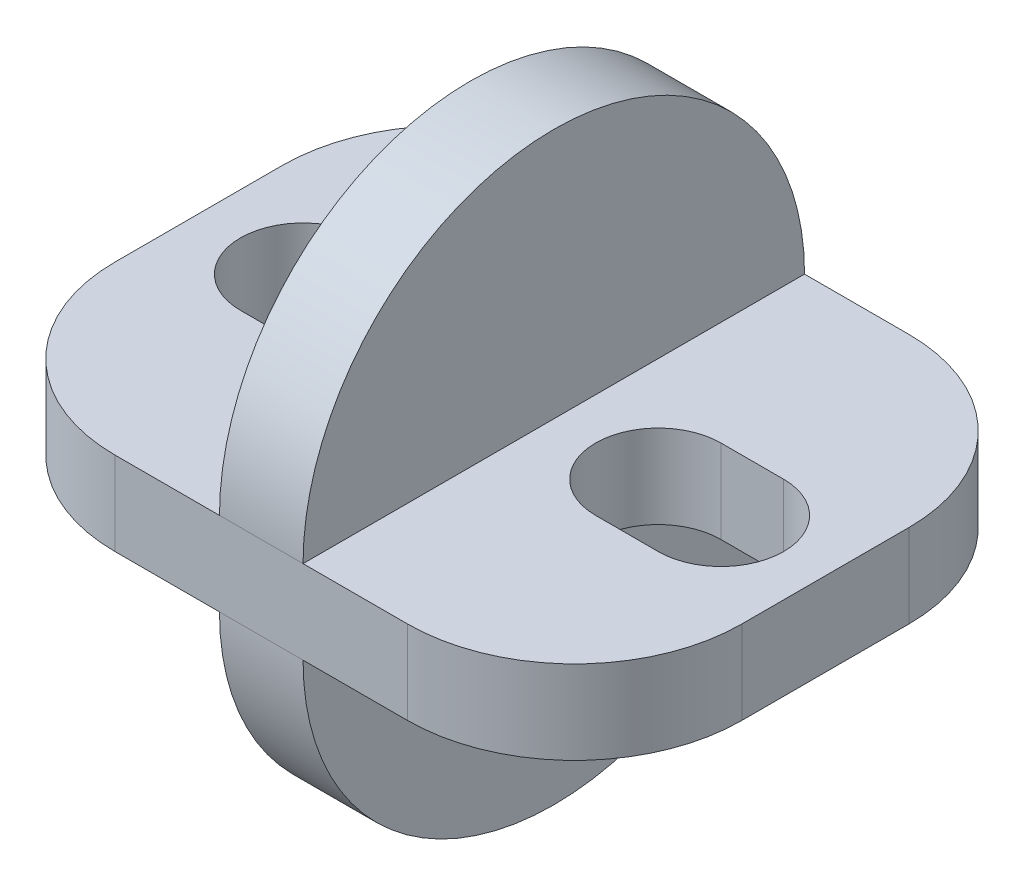
SolidWorks part; units mm, degrees
ref_plane "Alzado" through (0, 0, 0) normal (0, 0, 1) x (1, 0, 0)
ref_plane "Planta" through (0, 0, 0) normal (0, 1, 0) x (1, 0, 0)
ref_plane "Vista lateral" through (0, 0, 0) normal (1, 0, 0) x (0, 0, -1)
sketch "Croquis1" plane through (0, 0, 0) normal (0, 1, 0) x (1, 0, 0)
  line L1 (75, -60) -> (-75, -60)
  line L2 (75, -60) -> (75, 60)
  line L3 (75, 60) -> (-75, 60)
  line L4 (-75, -60) -> (-75, 60)
  line L5 (75, -60) -> (-75, 60) construction
  line L6 (75, 60) -> (-75, -60) construction
  point P0 (0, 0)
  dimension "D1" = 150
  dimension "D2" = 120
extrude "Saliente-Extruir1" add sketch "Croquis1" along normal blind 20
fillet "Redondeo1" radius 40 4 edges at (75, 10, 60) (75, 10, -60) (-75, 10, -60) (-75, 10, 60)
sketch "Croquis3" plane through (0, 0, 0) normal (1, 0, 0) x (0, 0, -1)
  line L0 (-60, 20) -> (60, 20)
  line L1 (60, 0) -> (-60, 0)
  arc A0 (-60, 20) -> (60, 20) centre (0, 20) cw
  arc A2 (-60, 0) -> (60, 0) centre (0, 0) ccw
  dimension "D1" = 60
  dimension "D2" = 60
extrude "Saliente-Extruir3" add sketch "Croquis3" along normal mid plane 20
sketch "Croquis4" plane through (0, 20, 0) normal (0, 1, 0) x (1, 0, 0)
  line L0 (-50, 0) -> (-35, 0) construction
  line L1 (-50, 15) -> (-35, 15)
  line L2 (-50, -15) -> (-35, -15)
  line L3 (50, 0) -> (35, 0) construction
  line L4 (50, -15) -> (35, -15)
  line L5 (50, 15) -> (35, 15)
  line L6 (-10, -60) -> (-10, 60) construction
  line L7 (10, -60) -> (10, 60) construction
  arc A0 (-50, 15) -> (-50, -15) centre (-50, 0) ccw
  arc A1 (-35, -15) -> (-35, 15) centre (-35, 0) ccw
  arc A2 (50, -15) -> (50, 15) centre (50, 0) ccw
  arc A3 (35, 15) -> (35, -15) centre (35, 0) ccw
  point P3 (-42.5, 0)
  point P8 (42.5, 0)
  dimension "D4" = 15
  dimension "D6" = 15
  dimension "D1" = 25
  dimension "D2" = 25
  dimension "D3" = 15
  dimension "D5" = 15
extrude "Cortar-Extruir1" cut sketch "Croquis4" against normal mid plane 67
